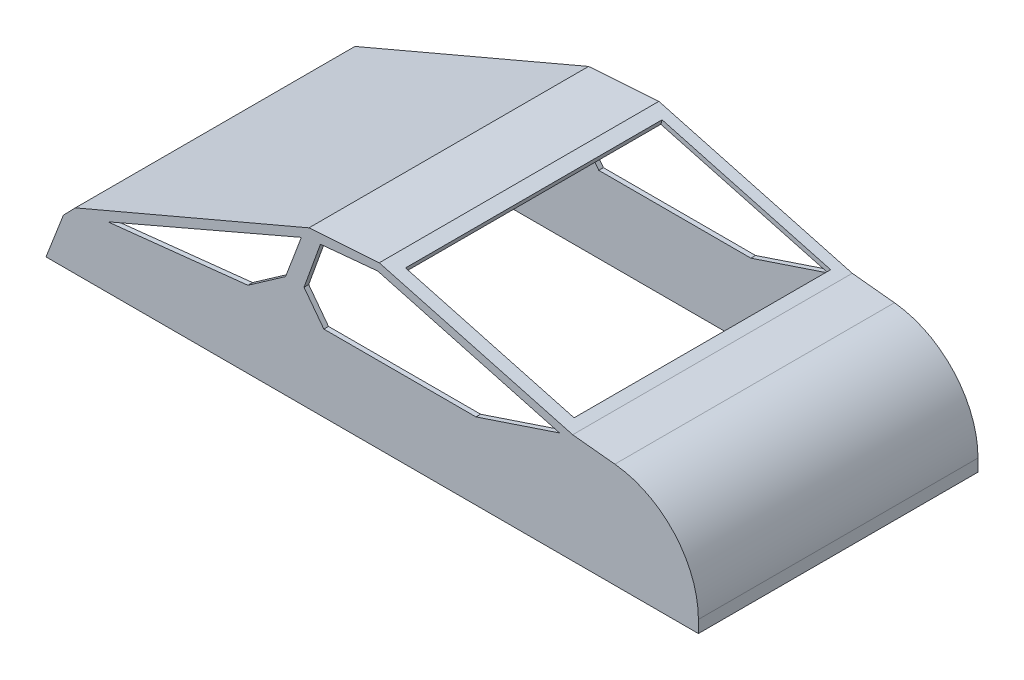
SolidWorks part; units mm, degrees
ref_plane "前视基准面" through (0, 0, 0) normal (0, 0, 1) x (1, 0, 0)
ref_plane "上视基准面" through (0, 0, 0) normal (0, 1, 0) x (1, 0, 0)
ref_plane "右视基准面" through (0, 0, 0) normal (1, 0, 0) x (0, 0, -1)
sketch "草图1" plane through (0, 0, 0) normal (0, 0, 1) x (1, 0, 0)
  line L0 (-402.1869, -155.169) -> (297.8131, -155.169)
  line L1 (297.8131, -155.169) -> (297.8131, -142.0165)
  line L2 (208.165, -42.5537) -> (162.9252, -37.8452)
  line L3 (162.9252, -37.8452) -> (-44.6063, 18.1804)
  line L4 (-120.0255, 12.933) -> (-370.7124, -93.8264)
  line L5 (-383.5292, -107.0678) -> (-402.1869, -155.169)
  line L6 (-370.7124, -93.8264) -> (-383.5292, -107.0678)
  line L7 (-44.6063, 18.1804) -> (-120.0255, 12.933)
  arc A0 (208.165, -42.5537) -> (297.8131, -142.0165) centre (197.8131, -142.0165) cw
  point P5 (-83.2238, 28.6056)
  point P6 (-379.9129, -97.7446)
  dimension "D2" = 100
  dimension "D1" = 700
sketch "草图2" plane through (0, 0, 0) normal (0, 0, 1) x (1, 0, 0)
extrude "凸台-拉伸1" add sketch "草图1" along normal blind 300
shell "抽壳2" thickness 5
sketch "草图3" plane through (0, 0, 0) normal (0, 0, -1) x (-1, 0, 0)
  line L0 (145.1463, -44.9213) -> (128.1651, 0)
  line L1 (145.1463, -44.9213) -> (185.5134, -73.1563)
  line L2 (185.5134, -73.1563) -> (335.8199, -89.3556)
  line L4 (107.7359, 3.9007) -> (125.3331, -44.9213)
  line L6 (125.3331, -44.9213) -> (104.0805, -73.1563)
  line L7 (104.0805, -73.1563) -> (-59.1594, -73.1563)
  line L8 (-59.1594, -73.1563) -> (-148.8254, -43.2217)
  line L11 (-148.8254, -43.2217) -> (46.2378, 9.6657)
  line L12 (46.2378, 9.6657) -> (107.7359, 3.9007)
  line L13 (128.1651, 0) -> (335.8199, -89.3556)
extrude "切除-拉伸1" cut sketch "草图3" against normal blind 300
sketch "草图4" plane through (1.5446, 5.7214, 0) normal (0.2606, 0.9654, 0) x (0.9654, -0.2606, 0)
  line L1 (-32.4338, -11.4175) -> (154.9333, -11.4175)
  line L2 (-32.4338, -11.4175) -> (-32.4338, -286.6834)
  line L3 (-32.4338, -286.6834) -> (154.9333, -286.6834)
  line L4 (154.9333, -11.4175) -> (154.9333, -286.6834)
extrude "切除-拉伸2" cut sketch "草图4" against normal blind 10
